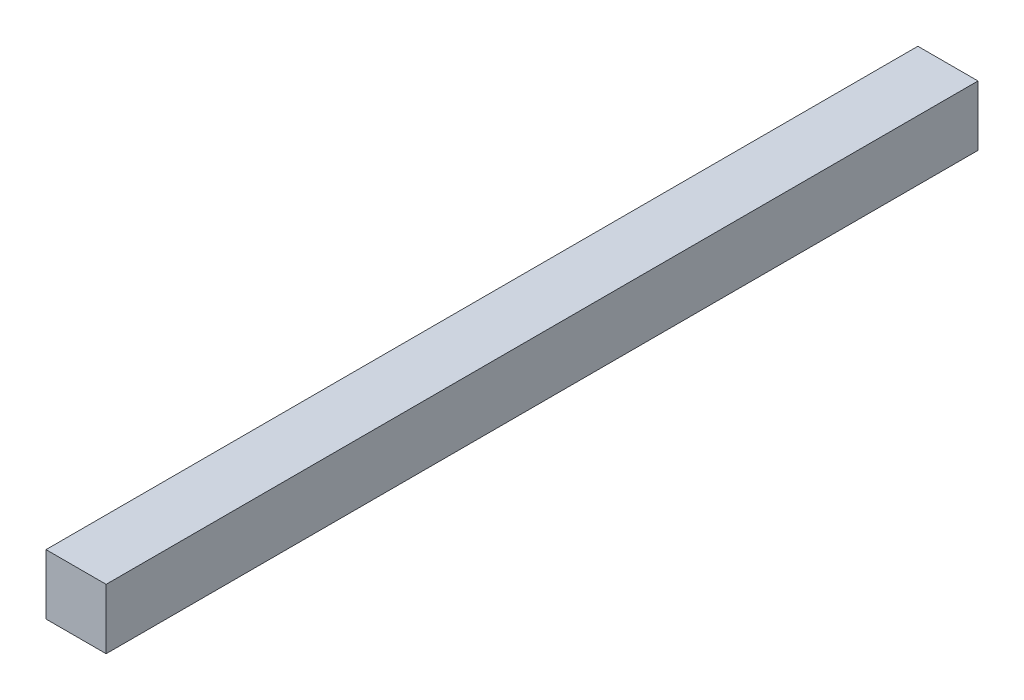
SolidWorks part; units mm, degrees
material "Balsa"
ref_plane "Front" through (0, 0, 0) normal (0, 0, 1) x (1, 0, 0)
ref_plane "Top" through (0, 0, 0) normal (0, 1, 0) x (1, 0, 0)
ref_plane "Right" through (0, 0, 0) normal (1, 0, 0) x (0, 0, -1)
sketch "Esboço1" plane through (0, 0, 0) normal (0, 1, 0) x (1, 0, 0)
  line L1 (3, -43.5) -> (-3, -43.5)
  line L2 (3, -43.5) -> (3, 43.5)
  line L3 (3, 43.5) -> (-3, 43.5)
  line L4 (-3, -43.5) -> (-3, 43.5)
  line L5 (3, -43.5) -> (-3, 43.5) construction
  line L6 (3, 43.5) -> (-3, -43.5) construction
  point P0 (0, 0)
  dimension "D1" = 6
  dimension "D2" = 87
extrude "Ressalto-extrusão1" add sketch "Esboço1" along normal blind 6
